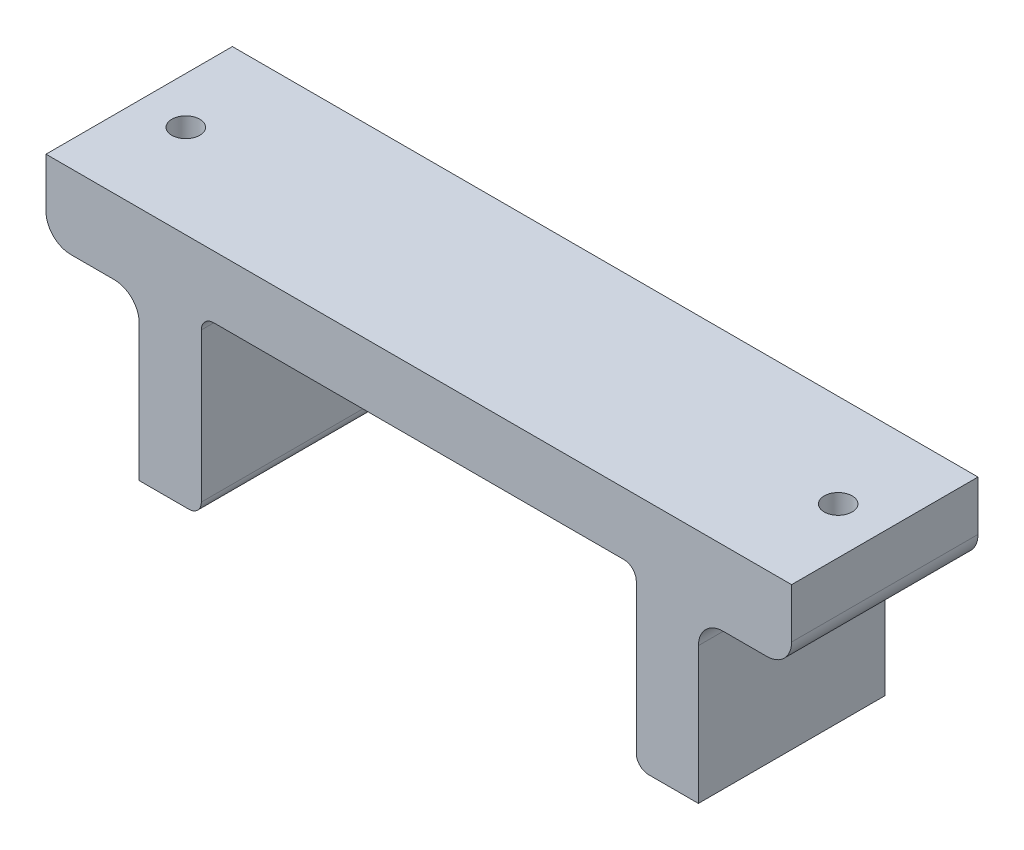
SolidWorks part; units mm, degrees
ref_plane "Front Plane" through (0, 0, 0) normal (0, 0, 1) x (1, 0, 0)
ref_plane "Top Plane" through (0, 0, 0) normal (0, 1, 0) x (1, 0, 0)
ref_plane "Right Plane" through (0, 0, 0) normal (1, 0, 0) x (0, 0, -1)
sketch "Sketch1" plane through (0, 0, 0) normal (0, 0, 1) x (1, 0, 0)
  line L2 (-35, -12) -> (-35, 12)
  line L3 (-33, 14) -> (33, 14)
  line L4 (35, -12) -> (35, 12)
  line L5 (-35, -14) -> (35, 14) construction
  line L6 (-35, 14) -> (35, -14) construction
  line L7 (45, -14) -> (45, 8)
  line L8 (-33, 24) -> (33, 24)
  line L9 (-45, -14) -> (-45, 8)
  line L10 (-33, 24) -> (-60, 24)
  line L11 (-60, 24) -> (-60, 16)
  line L12 (-56, 12) -> (-49, 12)
  line L13 (33, 24) -> (60, 24)
  line L14 (60, 24) -> (60, 16)
  line L15 (56, 12) -> (49, 12)
  line L16 (45, -12) -> (45, 12) construction
  line L17 (-45, -12) -> (-45, 12) construction
  line L18 (35, -12) -> (35, 12) construction
  line L24 (-35, -12) -> (-35, 12) construction
  line L25 (-33, -14) -> (33, -14) construction
  line L26 (-33, -24) -> (33, -24) construction
  line L27 (-37, -14) -> (-45, -14)
  line L28 (37, -14) -> (45, -14)
  arc A2 (33, 14) -> (35, 12) centre (33, 12) cw
  arc A3 (-35, 12) -> (-33, 14) centre (-33, 12) cw
  arc A8 (-45, 12) -> (-33, 24) centre (-33, 12) cw construction
  arc A9 (33, 24) -> (45, 12) centre (33, 12) cw construction
  arc A10 (60, 16) -> (56, 12) centre (56, 16) cw
  arc A11 (45, 8) -> (49, 12) centre (49, 8) cw
  arc A12 (-49, 12) -> (-45, 8) centre (-49, 8) cw
  arc A13 (-60, 16) -> (-56, 12) centre (-56, 16) ccw
  arc A16 (-33, -14) -> (-35, -12) centre (-33, -12) cw construction
  arc A17 (33, -14) -> (35, -12) centre (33, -12) ccw construction
  arc A18 (33, -24) -> (45, -12) centre (33, -12) ccw construction
  arc A19 (-33, -24) -> (-45, -12) centre (-33, -12) cw construction
  arc A20 (35, -12) -> (37, -14) centre (37, -12) ccw
  arc A21 (-35, -12) -> (-37, -14) centre (-37, -12) cw
  point P0 (0, 0)
  dimension "D3" = 2
  dimension "D7" = 4
  dimension "D1" = 70
  dimension "D2" = 28
  dimension "D5" = 15
  dimension "D6" = 15
  dimension "D4" = 10
extrude "Boss-Extrude1" add sketch "Sketch1" along normal blind 30
sketch "Sketch2" plane through (0, 12, 0) normal (0, -1, 0) x (1, 0, 0)
  line L0 (-52.5, 29) -> (-52.5, 1) construction
  line L3 (52.5, 29) -> (52.5, 1) construction
  circle A0 centre (-52.5, 15) radius 5
  circle A1 centre (52.5, 15) radius 5
  point P4 (0, 0)
  point P5 (0, 0)
  point P6 (0, 0)
  point P9 (-52.5, 15)
  point P17 (0, 0)
  dimension "D1" = 10
extrude "Cut-Extrude1" cut sketch "Sketch2" against normal blind 4 and the other way through all
sketch "Sketch3" plane through (0, 16, 0) normal (0, -1, 0) x (1, 0, 0)
  circle A0 centre (-52.5, 15) radius 2.25
  circle A1 centre (52.5, 15) radius 2.25
  dimension "D1" = 4.5
extrude "Cut-Extrude2" cut sketch "Sketch3" against normal through all
chamfer "Chamfer1" distance 1.5 angle 45 2 edges at (-50.25, 16, 15) (54.75, 16, 15)
sketch "Sketch4" plane through (0, -14, 0) normal (0, -1, 0) x (1, 0, 0)
  line L0 (-45, 15) -> (45, 15) construction
  line L1 (-45, 30) -> (-45, 0) construction
  line L2 (45, 30) -> (45, 0) construction
  circle A0 centre (-40, 15) radius 1.355
  circle A1 centre (40, 15) radius 1.355
  point P10 (0, 0)
  point P11 (0, 0)
  dimension "D1" = 2.71
  dimension "D2" = 5
  dimension "D3" = 5
extrude "Cut-Extrude3" cut sketch "Sketch4" against normal blind 10
